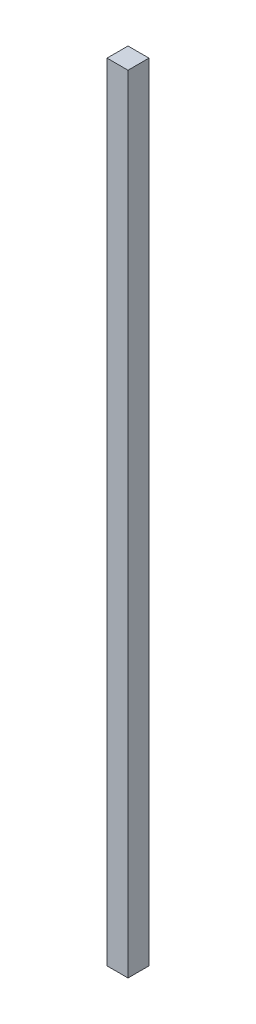
SolidWorks part; units mm, degrees
ref_plane "Front Plane" through (0, 0, 0) normal (0, 0, 1) x (1, 0, 0)
ref_plane "Top Plane" through (0, 0, 0) normal (0, 1, 0) x (1, 0, 0)
ref_plane "Right Plane" through (0, 0, 0) normal (1, 0, 0) x (0, 0, -1)
sketch "Sketch1" plane through (0, 0, 0) normal (0, 1, 0) x (1, 0, 0)
  line L1 (-2, 2) -> (2, 2)
  line L2 (-2, 2) -> (-2, -2)
  line L3 (-2, -2) -> (2, -2)
  line L4 (2, 2) -> (2, -2)
  line L5 (-2, 2) -> (2, -2) construction
  line L6 (-2, -2) -> (2, 2) construction
  point P0 (0, 0)
  dimension "D1" = 4
  dimension "D2" = 4
extrude "Boss-Extrude1" add sketch "Sketch1" along normal blind 150
